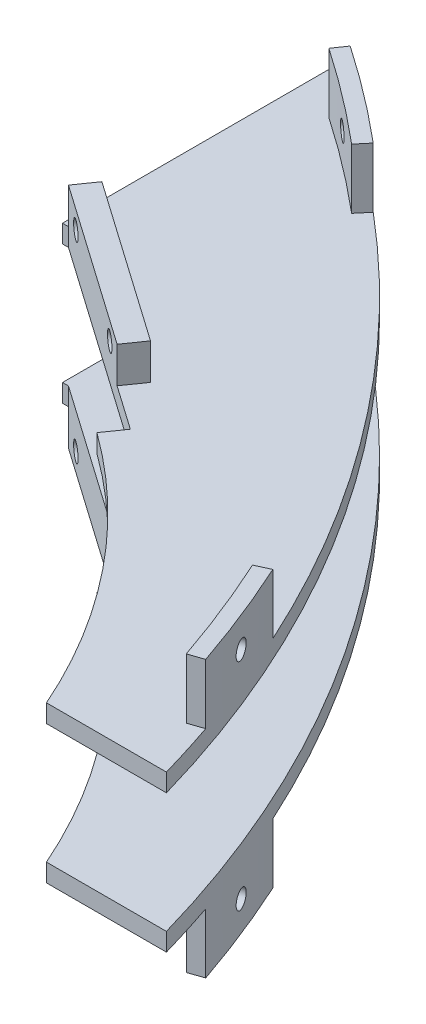
SolidWorks part; units mm, degrees
ref_plane "Front Plane" through (0, 0, 0) normal (0, 0, 1) x (1, 0, 0)
ref_plane "Top Plane" through (0, 0, 0) normal (0, 1, 0) x (1, 0, 0)
ref_plane "Right Plane" through (0, 0, 0) normal (1, 0, 0) x (0, 0, -1)
sketch "Sketch1" plane through (0, 0, 0) normal (0, 1, 0) x (1, 0, 0)
  line L0 (0, 0) -> (20, 0)
  line L1 (-67.91, 115.58) -> (-67.91, 72.58)
  arc A0 (0, 0) -> (-67.91, 72.58) centre (-137.2997, -60.4052) ccw
  arc A1 (20, 0) -> (-67.91, 115.58) centre (-172.2812, -55.0267) ccw
  dimension "D1" = 150
  dimension "D5" = 200
  dimension "D2" = 67.91
  dimension "D3" = 20
  dimension "D4" = 43
  dimension "D6" = 72.58
extrude "Boss-Extrude1" add sketch "Sketch1" along normal blind 3
sketch "Sketch2" plane through (0, 0, 0) normal (0, -1, 0) x (1, 0, 0)
  line L0 (-66.91, -72.0534) -> (-66.91, -70.5834) construction
  line L1 (-66.91, -70.5834) -> (-32.5056, -46.4932)
  line L2 (-67.91, -115.58) -> (-67.91, -72.58) construction
  line L3 (-66.91, -70.5834) -> (-67.91, -71.2836)
  line L4 (-67.91, -71.2836) -> (-67.91, -76.1667)
  line L5 (-32.5056, -51.3763) -> (-32.5056, -46.4932)
  line L6 (-67.91, -76.1667) -> (-32.5056, -51.3763)
  arc A0 (-67.91, -72.58) -> (0, 0) centre (-137.2997, 60.4052) ccw construction
  dimension "D5" = 4
  dimension "D1" = 1.47
  dimension "D2" = 1
  dimension "D3" = 125
  dimension "D4" = 42
extrude "Boss-Extrude2" add sketch "Sketch2" along normal blind 6
sketch "Sketch3" plane through (13.4449, 0, -19.2014) normal (0.5736, 0, -0.8192) x (-0.8192, 0, -0.5736)
  line L0 (121.9226, 3) -> (-16.383, 3) construction
  line L1 (99.3161, -6) -> (99.3161, 0) construction
  line L2 (53.2944, -6) -> (62.2961, -6)
  line L3 (99.3161, -6) -> (56.0953, -6) construction
  line L4 (62.2961, -6) -> (62.2961, 0)
  line L5 (-16.383, 0) -> (121.9226, 0) construction
  line L6 (62.2961, 0) -> (53.2944, 0)
  line L7 (53.2944, 0) -> (53.2944, -6)
  line L8 (99.3161, -6) -> (99.3161, 0)
  line L9 (99.3161, 0) -> (95.2961, 0)
  line L10 (95.2961, 0) -> (95.2961, -6)
  line L11 (95.2961, -6) -> (99.3161, -6)
  circle A0 centre (90.2961, -3) radius 1.5
  circle A1 centre (67.2961, -3) radius 1.5
  dimension "D1" = 6
  dimension "D3" = 3
  dimension "D2" = 9.02
  dimension "D4" = 23
  dimension "D5" = 5
  dimension "D6" = 5
extrude "Cut-Extrude1" cut sketch "Sketch3" against normal through all
sketch "Sketch5" plane through (0, 0, 0) normal (0, 1, 0) x (1, 0, 0)
  line L0 (-66.9113, 70.5843) -> (-67.91, 70.5843)
  line L1 (-67.91, 70.5843) -> (-67.91, 72.58)
  line L2 (-66.9113, 70.5843) -> (-32.5056, 46.4932)
  line L3 (-32.5056, 46.4932) -> (-34.7999, 43.2166)
  arc A1 (0, 0) -> (-67.91, 72.58) centre (-137.2997, -60.4052) ccw
  arc A2 (0, 0) -> (-67.91, 72.58) centre (-137.2997, -60.4052) ccw construction
  arc A3 (-34.7999, 43.2166) -> (0, 0) centre (-97.5095, -42.8995) cw
  dimension "D1" = 4
extrude "Boss-Extrude3" add sketch "Sketch5" along normal up to surface (3 mm away) up to face at (-24.6933, 3, -50.5522)
sketch "Sketch6" plane through (0, 0, 0) normal (0, -1, 0) x (1, 0, 0)
  line L0 (0, 0) -> (20, 0) construction
  line L1 (-67.91, -115.58) -> (-67.91, -70.5843) construction
  line L2 (17.3432, 0) -> (20, 0)
  line L3 (-67.91, -112.58) -> (-67.91, -115.58)
  line L4 (-60.9522, -108.0414) -> (-59.5128, -110.1498)
  line L5 (14.593, -8.7181) -> (17.0092, -9.5423)
  line L6 (7.2921, -27.0634) -> (9.6139, -28.1248)
  line L7 (-43.5796, -98.0612) -> (-45.2225, -96.1071)
  arc A0 (-67.91, -115.58) -> (20, 0) centre (-172.2812, 55.0267) ccw
  arc A1 (17.3432, 0) -> (-67.91, -112.58) centre (-172.2812, 55.0267) cw
  arc A2 (-67.91, -115.58) -> (20, 0) centre (-172.2812, 55.0267) ccw construction
  arc M11 (-67.91, -115.58) -> (20, 0) centre (-172.2812, 55.0267) ccw
  dimension "D1" = 3
  dimension "D2" = 10
  dimension "D3" = 10
  dimension "D4" = 20
  dimension "D5" = 20
extrude "Boss-Extrude4" add sketch "Sketch6" along normal blind 10 contours L7 A1 L4 M11 | L5 A1 L6 M11
sketch "Sketch7" plane through (0, -10, 0) normal (0, -1, 0) x (1, 0, 0)
  line L0 (-51.395, -104.3048) -> (-172.2812, 55.0267) construction
  line L1 (-172.2812, 55.0267) -> (13.544, -18.926) construction
  arc A2 (9.6139, -28.1248) -> (17.0092, -9.5423) centre (-172.2812, 55.0267) ccw construction
  arc A3 (-59.5128, -110.1498) -> (-43.5796, -98.0612) centre (-172.2812, 55.0267) ccw construction
ref_plane "Plane1" through (-51.395, -10, -104.3048) normal (0.6044, 0, -0.7967) x (-0.7967, 0, -0.6044)
sketch "Sketch8" plane through (-51.395, -10, -104.3048) normal (0.6044, 0, -0.7967) x (-0.7967, 0, -0.6044)
  line L0 (10, 10) -> (-10, 0) construction
  circle A0 centre (0, 5) radius 1.5
  dimension "D1" = 3
extrude "Cut-Extrude2" cut sketch "Sketch8" against normal through all
ref_plane "Plane2" through (18.1943, 0, -7.2408) normal (0.9291, 0, -0.3698) x (-0.3698, 0, -0.9291)
sketch "Sketch9" plane through (18.1943, 0, -7.2408) normal (0.9291, 0, -0.3698) x (-0.3698, 0, -0.9291)
  line L0 (2.5766, 0) -> (22.5766, -10) construction
  line L1 (115.9163, -10) -> (12.5766, -10) construction
  line L2 (22.5766, -10) -> (22.5766, 0) construction
  circle A0 centre (12.5766, -5) radius 1.5
  dimension "D1" = 3
extrude "Cut-Extrude3" cut sketch "Sketch9" against normal through all
ref_plane "Plane3" through (0, 13, 0) normal (0, 1, 0) x (1, 0, 0)
mirror "Mirror2" about plane through (0, 13, 0) normal (0, 1, 0) of bodies 107
